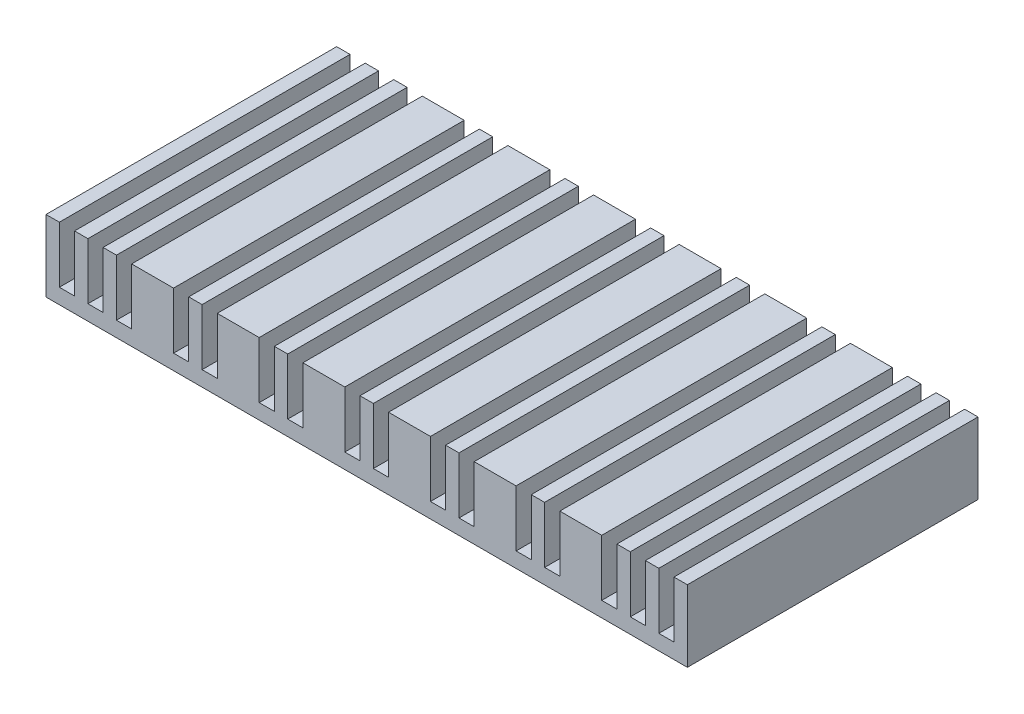
SolidWorks part; units mm, degrees
ref_plane "Ön Düzlem" through (0, 0, 0) normal (0, 0, 1) x (1, 0, 0)
ref_plane "Üst Düzlem" through (0, 0, 0) normal (0, 1, 0) x (1, 0, 0)
ref_plane "Sağ Düzlem" through (0, 0, 0) normal (1, 0, 0) x (0, 0, -1)
sketch "Çizim1" plane through (0, 0, 0) normal (0, 0, 1) x (1, 0, 0)
  line L0 (0, 0) -> (0, 7.8)
  line L1 (0, 7.8) -> (1.85, 7.8)
  line L2 (1.85, 7.8) -> (1.85, 0)
  line L3 (1.85, 0) -> (3.95, 0)
  line L4 (3.95, 0) -> (3.95, 7.8)
  line L5 (3.95, 7.8) -> (5.8, 7.8)
  line L6 (5.8, 7.8) -> (5.8, 0)
  line L7 (5.8, 0) -> (7.9, 0)
  line L8 (7.9, 0) -> (7.9, 7.8)
  line L9 (7.9, 7.8) -> (9.75, 7.8)
  line L10 (9.75, 7.8) -> (9.75, 0)
  line L11 (9.75, 0) -> (11.85, 0)
  line L12 (11.85, 0) -> (11.85, 7.8)
  line L13 (11.85, 7.8) -> (17.65, 7.8)
  line L14 (17.65, 7.8) -> (17.65, 0)
  line L15 (17.65, 0) -> (19.75, 0)
  line L16 (19.75, 0) -> (19.75, 7.8)
  line L17 (19.75, 7.8) -> (21.6, 7.8)
  line L18 (21.6, 7.8) -> (21.6, 0)
  line L19 (21.6, 0) -> (23.7, 0)
  line L20 (23.7, 0) -> (23.7, 7.8)
  line L21 (23.7, 7.8) -> (29.5, 7.8)
  line L22 (29.5, 7.8) -> (29.5, 0)
  line L23 (29.5, 0) -> (31.6, 0)
  line L24 (31.6, 0) -> (31.6, 7.8)
  line L25 (33.45, 7.8) -> (33.45, 0)
  line L26 (31.6, 7.8) -> (33.45, 7.8)
  line L27 (33.45, 0) -> (35.55, 0)
  line L28 (35.55, 0) -> (35.55, 7.8)
  line L29 (35.55, 7.8) -> (41.35, 7.8)
  line L30 (41.35, 7.8) -> (41.35, 0)
  line L31 (41.35, 0) -> (43.45, 0)
  line L32 (43.45, 0) -> (43.45, 7.8)
  line L33 (45.3, 7.8) -> (45.3, 0)
  line L34 (43.45, 7.8) -> (45.3, 7.8)
  line L35 (45.3, 0) -> (47.4, 0)
  line L36 (47.4, 0) -> (47.4, 7.8)
  line L37 (47.4, 7.8) -> (53.2, 7.8)
  line L38 (53.2, 7.8) -> (53.2, 0)
  line L39 (53.2, 0) -> (55.3, 0)
  line L40 (55.3, 0) -> (55.3, 7.8)
  line L41 (57.15, 7.8) -> (57.15, 0)
  line L42 (55.3, 7.8) -> (57.15, 7.8)
  line L43 (57.15, 0) -> (59.25, 0)
  line L44 (59.25, 0) -> (59.25, 7.8)
  line L45 (59.25, 7.8) -> (65.05, 7.8)
  line L46 (65.05, 7.8) -> (65.05, 0)
  line L47 (65.05, 0) -> (67.15, 0)
  line L48 (67.15, 0) -> (67.15, 7.8)
  line L49 (69, 7.8) -> (69, 0)
  line L50 (67.15, 7.8) -> (69, 7.8)
  line L51 (69, 0) -> (71.1, 0)
  line L52 (71.1, 0) -> (71.1, 7.8)
  line L53 (71.1, 7.8) -> (76.9, 7.8)
  line L54 (76.9, 7.8) -> (76.9, 0)
  line L55 (76.9, 0) -> (79, 0)
  line L56 (79, 0) -> (79, 7.8)
  line L57 (80.85, 7.8) -> (80.85, 0)
  line L58 (79, 7.8) -> (80.85, 7.8)
  line L59 (80.85, 0) -> (82.95, 0)
  line L60 (82.95, 0) -> (82.95, 7.8)
  line L61 (84.8, 7.8) -> (84.8, 0)
  line L62 (82.95, 7.8) -> (84.8, 7.8)
  line L63 (84.8, 0) -> (86.9, 0)
  line L64 (86.9, 0) -> (86.9, 7.8)
  line L65 (88.75, 7.8) -> (88.75, 0)
  line L66 (86.9, 7.8) -> (88.75, 7.8)
  line L67 (0, 0) -> (0, -2.1)
  line L68 (0, -2.1) -> (88.75, -2.1)
  line L69 (88.75, -2.1) -> (88.75, 0)
  dimension "D1" = 2.1
  dimension "D2" = 1.85
  dimension "D3" = 7.8
  dimension "D5" = 5.8
  dimension "D8" = 9.9
  dimension "D4" = 3
  dimension "D6" = 6
  dimension "D7" = 3
extrude "Yükseklik-Ekstrüzyon1" add sketch "Çizim1" along normal blind 40.22
